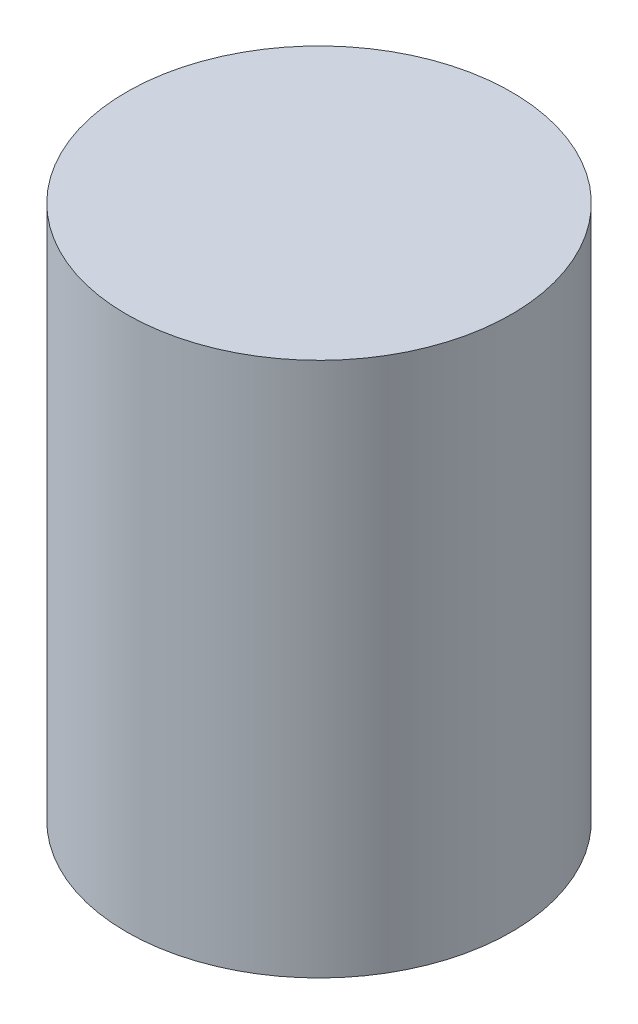
SolidWorks part; units mm, degrees
ref_plane "Front Plane" through (0, 0, 0) normal (0, 0, 1) x (1, 0, 0)
ref_plane "Top Plane" through (0, 0, 0) normal (0, 1, 0) x (1, 0, 0)
ref_plane "Right Plane" through (0, 0, 0) normal (1, 0, 0) x (0, 0, -1)
sketch "Sketch1" plane through (0, 0, 0) normal (0, 1, 0) x (1, 0, 0)
  circle A0 centre (0, 0) radius 64
  point P3 (0, 0)
  dimension "D1" = 128
extrude "Boss-Extrude1" add sketch "Sketch1" along normal blind 177.8
